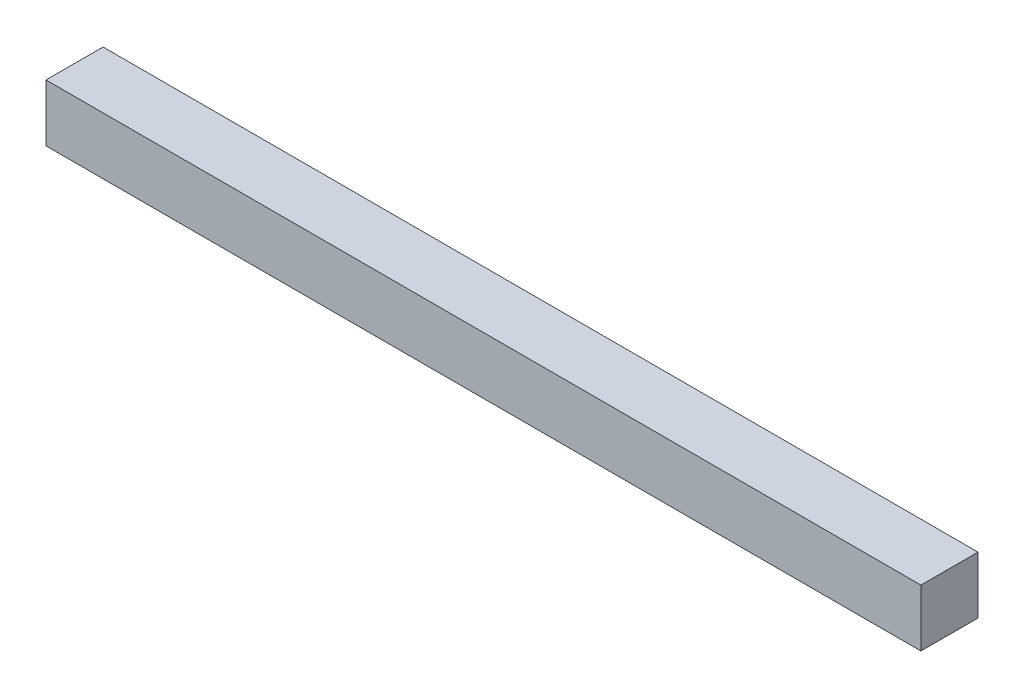
SolidWorks part; units mm, degrees
ref_plane "Front Plane" through (0, 0, 0) normal (0, 0, 1) x (1, 0, 0)
ref_plane "Top Plane" through (0, 0, 0) normal (0, 1, 0) x (1, 0, 0)
ref_plane "Right Plane" through (0, 0, 0) normal (1, 0, 0) x (0, 0, -1)
sketch "Sketch1" plane through (0, 0, 0) normal (1, 0, 0) x (0, 0, -1)
  line L1 (0, 0) -> (15, 0)
  line L2 (0, 0) -> (0, 15)
  line L3 (0, 15) -> (15, 15)
  line L4 (15, 0) -> (15, 15)
  dimension "D1" = 15
extrude "Boss-Extrude1" add sketch "Sketch1" along normal blind 229.8979
